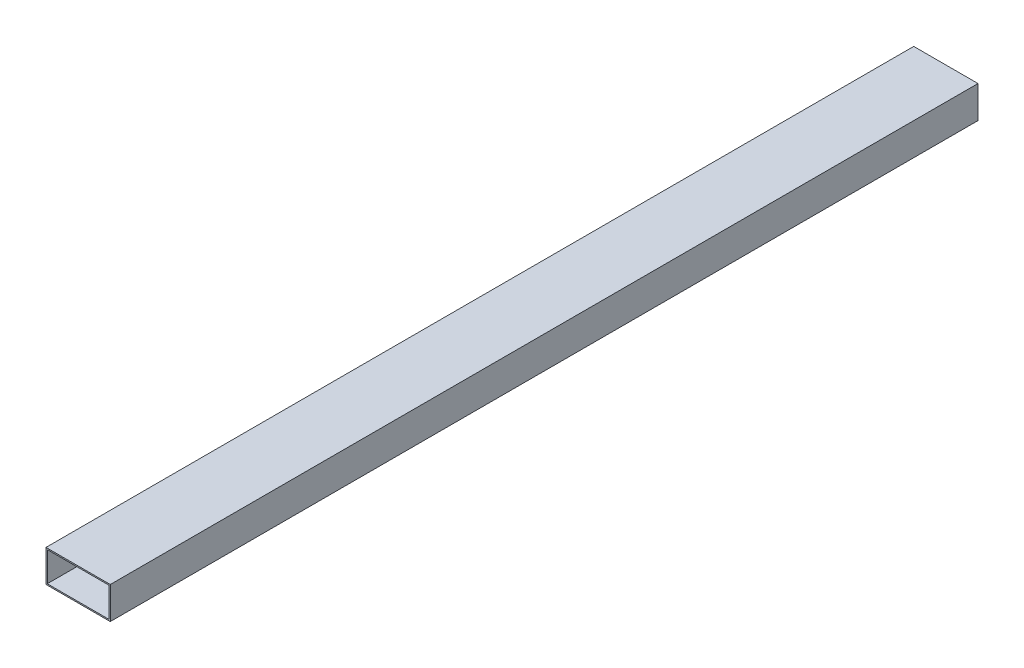
SolidWorks part; units mm, degrees
ref_plane "Alzado" through (0, 0, 0) normal (0, 0, 1) x (1, 0, 0)
ref_plane "Planta" through (0, 0, 0) normal (0, 1, 0) x (1, 0, 0)
ref_plane "Vista lateral" through (0, 0, 0) normal (1, 0, 0) x (0, 0, -1)
sketch "Croquis1" plane through (0, 0, 0) normal (0, 0, 1) x (1, 0, 0)
  line L1 (-107.863, 31.3707) -> (92.137, 31.3707)
  line L2 (-107.863, 31.3707) -> (-107.863, -68.6293)
  line L3 (-107.863, -68.6293) -> (92.137, -68.6293)
  line L4 (92.137, 31.3707) -> (92.137, -68.6293)
  line L5 (-103.863, 27.3707) -> (88.137, 27.3707)
  line L6 (-103.863, 27.3707) -> (-103.863, -64.6293)
  line L7 (-103.863, -64.6293) -> (88.137, -64.6293)
  line L8 (88.137, 27.3707) -> (88.137, -64.6293)
  dimension "D1" = 4
  dimension "D2" = 4
  dimension "D3" = 4
  dimension "D4" = 4
  dimension "D5" = 100
  dimension "D6" = 200
extrude "Saliente-Extruir1" add sketch "Croquis1" along normal blind 2700
